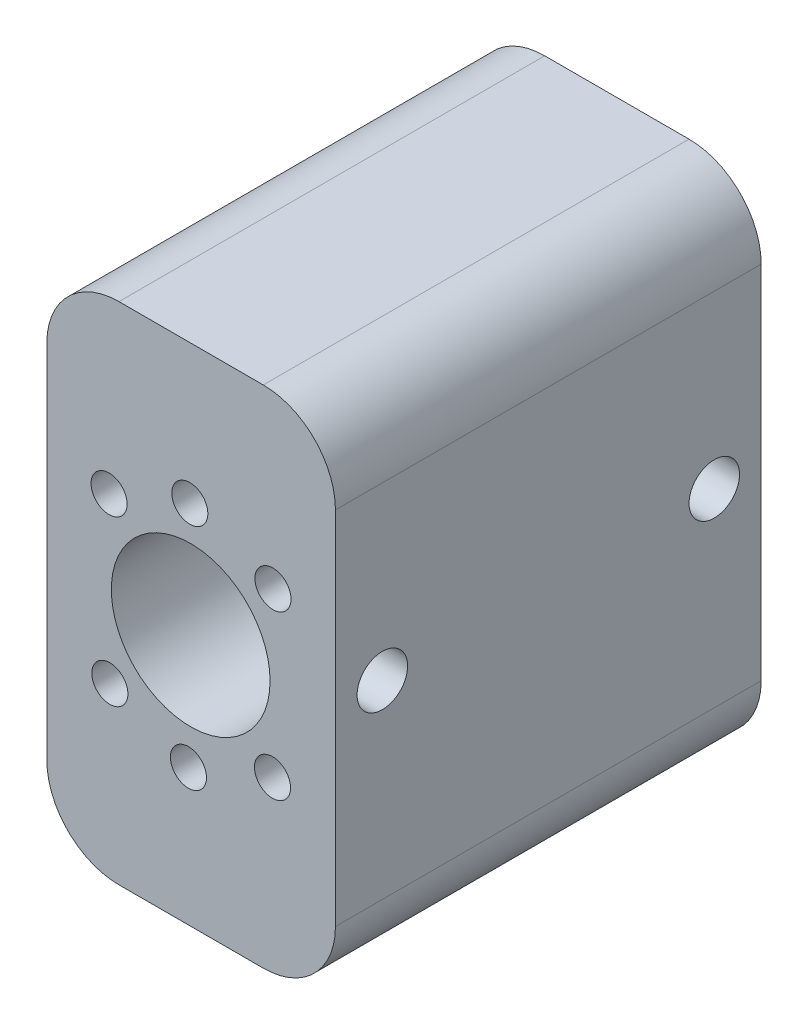
SolidWorks part; units mm, degrees
ref_plane "Front Plane" through (0, 0, 0) normal (0, 0, 1) x (1, 0, 0)
ref_plane "Top Plane" through (0, 0, 0) normal (0, 1, 0) x (1, 0, 0)
ref_plane "Right Plane" through (0, 0, 0) normal (1, 0, 0) x (0, 0, -1)
sketch "Sketch1" plane through (0, 0, 0) normal (0, 0, 1) x (1, 0, 0)
  line L0 (0.0608, 20.3128) -> (0.0608, -20.1872) construction
  line L1 (-14.9392, 0.0628) -> (15.0608, 0.0628) construction
  line L2 (-14.9392, 13.6666) -> (-14.9392, -13.541)
  line L3 (15.0608, 13.6666) -> (15.0608, -13.541)
  line L4 (0.0608, 20.3128) -> (0.0608, 35.0628) construction
  line L5 (-19.9392, 35.0628) -> (20.0608, 35.0628)
  line L6 (-19.9392, 35.0628) -> (-19.9392, -34.9372)
  line L7 (-19.9392, -34.9372) -> (20.0608, -34.9372)
  line L8 (20.0608, 35.0628) -> (20.0608, -34.9372)
  line L9 (-19.9392, 35.0628) -> (20.0608, -34.9372) construction
  line L10 (-19.9392, -34.9372) -> (20.0608, 35.0628) construction
  line L11 (0.0608, 0.0628) -> (20.0608, 0.0628) construction
  arc A0 (-14.9392, -13.541) -> (15.0608, -13.541) centre (0.0608, 0.0628) ccw
  arc A1 (15.0608, 13.6666) -> (-14.9392, 13.6666) centre (0.0608, 0.0628) ccw
  dimension "D1" = 40.5
  dimension "D2" = 30
  dimension "D3" = 20
  dimension "D4" = 35
sketch "Sketch2" plane through (0, 0, 0) normal (0, 0, 1) x (1, 0, 0)
  line L0 (0, -20.25) -> (0, 20.25) construction
  line L2 (15, 0) -> (-15, 0) construction
  line L6 (0, 0) -> (11.3137, -11.3137) construction
  circle A2 centre (0, 0) radius 11
  circle A3 centre (-11.3137, 11.3137) radius 2.5
  circle A4 centre (-0.1223, 15.7597) radius 2.5
  circle A5 centre (11.4027, 11.2637) radius 2.5
  circle A6 centre (11.3394, -11.4064) radius 2.5
  circle A7 centre (-0.3123, -16.0291) radius 2.5
  circle A8 centre (-11.2041, -11.4064) radius 2.5
  point P0 (0, -16)
  point P2 (11.3137, -11.3137)
  point P30 (-11.3137, -11.3137)
  point P32 (-11.3137, 11.3137)
  point P33 (0, 16)
  point P34 (11.3137, 11.3137)
  dimension "D2" = 45
  dimension "D3" = 16
extrude "Boss-Extrude1" add sketch "Sketch1" along normal blind 59 contours L5 L8 L7 L6
extrude "Cut-Extrude1" cut sketch "Sketch2" along normal through all
sketch "Sketch5" plane through (-19.9392, 0, 0) normal (-1, 0, 0) x (0, 0, 1)
  line L0 (59, 0.0628) -> (0, 0.0628) construction
  line L2 (29.5, 35.0628) -> (29.5, -34.9372) construction
  line L5 (29.5, 35.0628) -> (29.5, -34.9372) construction
  line L6 (59, 35.0628) -> (0, 35.0628) construction
  line L7 (59, -34.9372) -> (0, -34.9372) construction
  line L8 (0, 0.0628) -> (59, 0.0628) construction
  line L9 (0, 35.0628) -> (0, -34.9372) construction
  line L10 (59, 35.0628) -> (59, -34.9372) construction
  circle A0 centre (29.5, 0.0628) radius 2.55
  circle A1 centre (39.5, 0.0628) radius 2.55
  circle A2 centre (19.5, 0.0628) radius 2.55
  circle A3 centre (29.5, 10.0628) radius 2.55
  circle A4 centre (29.5, -9.9372) radius 2.55
  point P28 (29.5, 0.0628)
  dimension "D1" = 10
  dimension "D5" = 5.1
  dimension "D6" = 5.1
  dimension "D7" = 5.1
  dimension "D8" = 5.1
  dimension "D9" = 5.1
  dimension "D2" = 10
  dimension "D3" = 10
  dimension "D4" = 10
extrude "Cut-Extrude3" cut sketch "Sketch5" against normal blind 5
sketch "Sketch6" plane through (20.0608, 0, 0) normal (1, 0, 0) x (0, 0, -1)
  line L0 (-29.16, 3.046) -> (-29.16, -6.954) construction
  line L3 (-59.16, 3.046) -> (0.84, 3.046) construction
  point P0 (-6.16, 3.046)
  point P11 (-52.16, 3.046)
  dimension "D1" = 46
fillet "Fillet1" radius 10 1 edges at (20.0608, 35.0628, 29.5)
fillet "Fillet2" radius 10 1 edges at (20.0608, -34.9372, 29.5)
fillet "Fillet3" radius 10 1 edges at (-19.9392, -34.9372, 29.5)
fillet "Fillet4" radius 10 1 edges at (-19.9392, 35.0628, 29.5)
sketch "Sketch10" plane through (0, 0, 0) normal (1, 0, 0) x (0, 0, -1)
  line L0 (-58.9525, 1.34) -> (-0.0475, 1.34) construction
  line L3 (-29.5, 35.0628) -> (-29.5, -34.9372) construction
  line L4 (-59, 35.0628) -> (0, 35.0628) construction
  line L5 (0, -34.9372) -> (-59, -34.9372) construction
  circle A0 centre (-52.5, 1.34) radius 3.5
  circle A1 centre (-6.5, 1.34) radius 3.5
  point P10 (-29.5, 1.34)
  dimension "D1" = 7
  dimension "D2" = 7
  dimension "D3" = 23
  dimension "D4" = 23
  dimension "D5" = 1.34
extrude "Cut-Extrude4" cut sketch "Sketch10" against normal blind 5 from surface at 20.0608 starting at face at (20.0608, 0.0628, 29.5)
